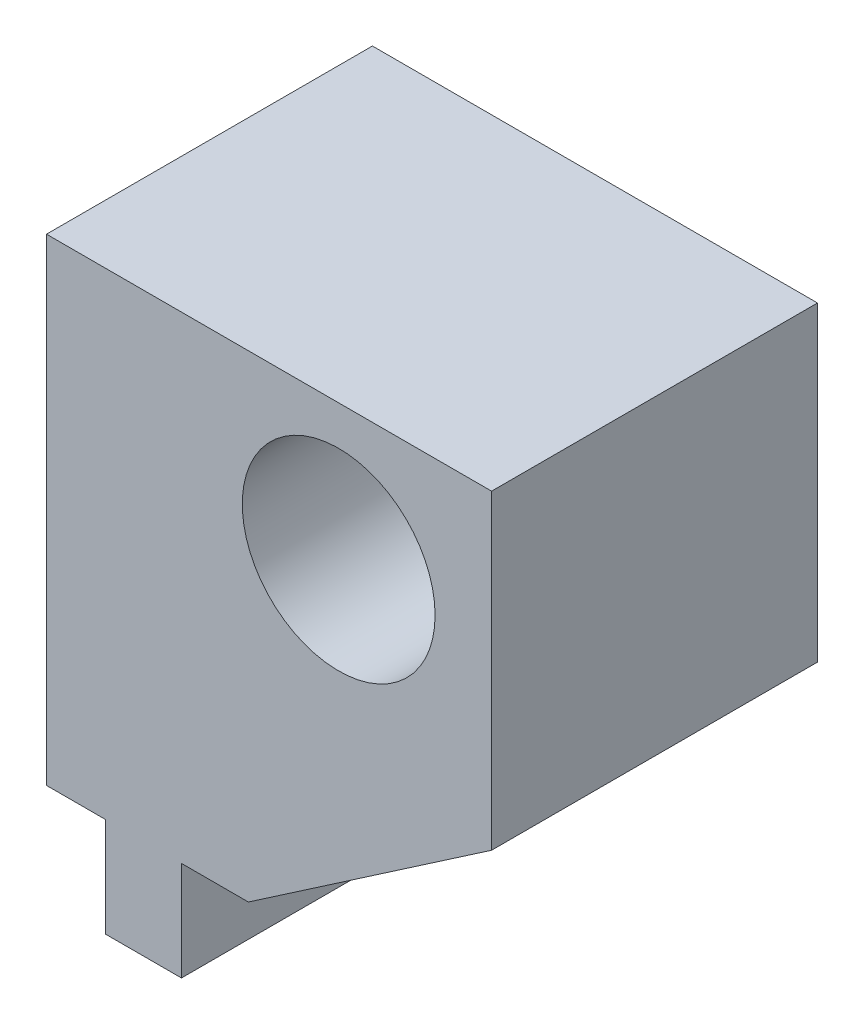
SolidWorks part; units mm, degrees
ref_plane "Front Plane" through (0, 0, 0) normal (0, 0, 1) x (1, 0, 0)
ref_plane "Top Plane" through (0, 0, 0) normal (0, 1, 0) x (1, 0, 0)
ref_plane "Right Plane" through (0, 0, 0) normal (1, 0, 0) x (0, 0, -1)
sketch "Sketch1" plane through (0, 0, 0) normal (0, 0, 1) x (1, 0, 0)
  line L0 (-11.4279, 15) -> (16.8902, 15)
  line L1 (16.8902, 15) -> (16.8902, 4.2909)
  line L2 (16.8902, 4.2909) -> (16.8902, -19.3555)
  line L3 (16.8902, -19.3555) -> (-9.9749, -37.7378)
  line L4 (-9.9749, -37.7378) -> (-17.3672, -37.7378)
  line L5 (-17.3672, -37.7378) -> (-17.3672, -48.7031)
  line L6 (-17.3672, -48.7031) -> (-25.7452, -48.7031)
  line L7 (-25.7452, -48.7031) -> (-25.7452, -37.7378)
  line L8 (-25.7452, -37.7378) -> (-32.2751, -37.7378)
  line L9 (-32.2751, -37.7378) -> (-32.2751, 11.1748)
  line L10 (-32.2751, 11.1748) -> (-32.2751, 15)
  line L11 (-32.2751, 15) -> (-11.4279, 15)
  circle A0 centre (0, 0) radius 10.65
  dimension "D1" = 21.3
  dimension "D2" = 15
extrude "Boss-Extrude1" add sketch "Sketch1" along normal blind 36
